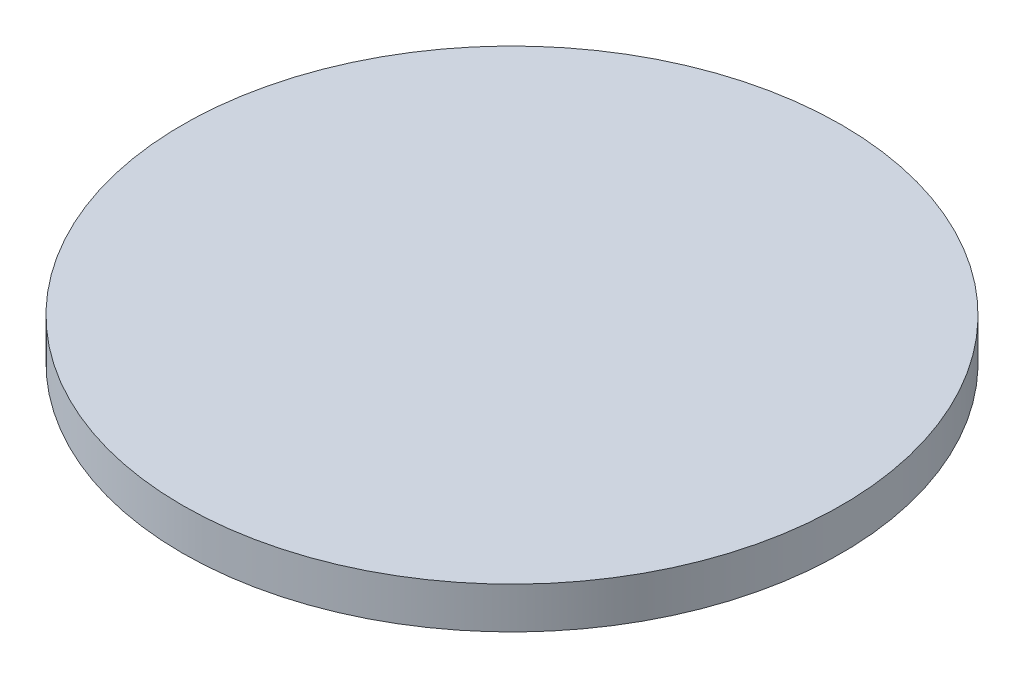
SolidWorks part; units mm, degrees
ref_plane "Front" through (0, 0, 0) normal (0, 0, 1) x (1, 0, 0)
ref_plane "Top" through (0, 0, 0) normal (0, 1, 0) x (1, 0, 0)
ref_plane "Right" through (0, 0, 0) normal (1, 0, 0) x (0, 0, -1)
sketch "Sketch2" plane through (0, 0, 0) normal (0, 1, 0) x (1, 0, 0)
  circle A0 centre (0, 0) radius 23.875
  dimension "D1" = 47.75
extrude "Boss-Extrude1" add sketch "Sketch2" along normal blind 3
